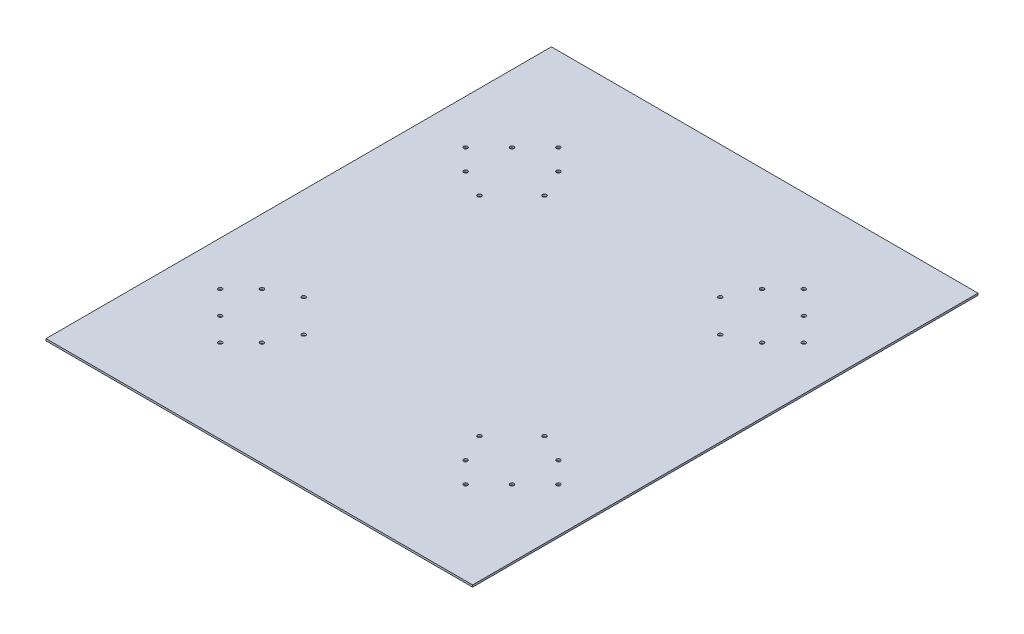
SolidWorks part; units mm, degrees
ref_plane "Front Plane" through (0, 0, 0) normal (0, 0, 1) x (1, 0, 0)
ref_plane "Top Plane" through (0, 0, 0) normal (0, 1, 0) x (1, 0, 0)
ref_plane "Right Plane" through (0, 0, 0) normal (1, 0, 0) x (0, 0, -1)
sketch "Sketch2" plane through (0, 1310.5484, 0) normal (0, 1, 0) x (1, 0, 0)
  line L0 (878.8182, -1232.4154) -> (956.6, -1310.1971) construction
  line L1 (740.7773, -1889.2272) -> (1390.7773, -1889.2272)
  line L2 (740.7773, -1889.2272) -> (740.7773, -1119.2272)
  line L3 (793.9654, -1691.1863) -> (878.8182, -1776.0391) construction
  line L4 (740.7773, -1119.2272) -> (1390.7773, -1119.2272)
  line L5 (1390.7773, -1889.2272) -> (1390.7773, -1119.2272)
  line L6 (740.7773, -1889.2272) -> (1390.7773, -1119.2272) construction
  line L7 (1337.5891, -1317.2682) -> (1252.7363, -1232.4154) construction
  line L11 (793.9654, -1691.1863) -> (878.8182, -1776.0391)
  line L15 (1337.5891, -1317.2682) -> (1252.7363, -1232.4154)
  line L16 (740.7773, -1119.2272) -> (1390.7773, -1889.2272) construction
  line L17 (836.3918, -1733.6127) -> (1295.1627, -1274.8418)
  line L18 (956.6, -1310.1971) -> (871.7472, -1395.0499) construction
  line L19 (871.7472, -1395.0499) -> (793.9654, -1317.2682) construction
  line L20 (793.9654, -1317.2682) -> (878.8182, -1232.4154) construction
  line L21 (1337.5891, -1317.2682) -> (1259.8074, -1395.0499) construction
  line L22 (1259.8074, -1395.0499) -> (1174.9546, -1310.1971) construction
  line L23 (1174.9546, -1310.1971) -> (1252.7363, -1232.4154) construction
  line L24 (1252.7363, -1232.4154) -> (1337.5891, -1317.2682) construction
  line L25 (1252.7363, -1776.0391) -> (1174.9546, -1698.2573) construction
  line L26 (1174.9546, -1698.2573) -> (1259.8074, -1613.4045) construction
  line L27 (1259.8074, -1613.4045) -> (1337.5891, -1691.1863) construction
  line L28 (1337.5891, -1691.1863) -> (1252.7363, -1776.0391) construction
  line L29 (871.7472, -1613.4045) -> (956.6, -1698.2573) construction
  line L30 (956.6, -1698.2573) -> (878.8182, -1776.0391) construction
  line L31 (878.8182, -1776.0391) -> (793.9654, -1691.1863) construction
  line L32 (793.9654, -1691.1863) -> (871.7472, -1613.4045) construction
  line L33 (878.8182, -1232.4154) -> (956.6, -1310.1971)
  line L34 (956.6, -1310.1971) -> (871.7472, -1395.0499)
  line L35 (871.7472, -1395.0499) -> (793.9654, -1317.2682)
  line L36 (793.9654, -1317.2682) -> (878.8182, -1232.4154)
  line L37 (1337.5891, -1317.2682) -> (1259.8074, -1395.0499)
  line L38 (1259.8074, -1395.0499) -> (1174.9546, -1310.1971)
  line L39 (1174.9546, -1310.1971) -> (1252.7363, -1232.4154)
  line L40 (1252.7363, -1232.4154) -> (1337.5891, -1317.2682)
  line L41 (1252.7363, -1776.0391) -> (1174.9546, -1698.2573)
  line L42 (1174.9546, -1698.2573) -> (1259.8074, -1613.4045)
  line L43 (1259.8074, -1613.4045) -> (1337.5891, -1691.1863)
  line L44 (1337.5891, -1691.1863) -> (1252.7363, -1776.0391)
  line L45 (871.7472, -1613.4045) -> (956.6, -1698.2573)
  line L46 (956.6, -1698.2573) -> (878.8182, -1776.0391)
  line L47 (878.8182, -1776.0391) -> (793.9654, -1691.1863)
  line L48 (793.9654, -1691.1863) -> (871.7472, -1613.4045)
  circle A1 centre (1249.2008, -1638.1533) radius 3
  circle A2 centre (1249.2008, -1638.1533) radius 3
  circle A3 centre (1199.7033, -1687.6507) radius 3
  circle A4 centre (1199.7033, -1687.6507) radius 3
  circle A5 centre (1220.9165, -1730.0771) radius 3
  circle A6 centre (1220.9165, -1730.0771) radius 3
  circle A7 centre (1252.7363, -1761.8969) radius 3
  circle A8 centre (1252.7363, -1761.8969) radius 3
  circle A9 centre (1288.0916, -1726.5416) radius 3
  circle A10 centre (1288.0916, -1726.5416) radius 3
  circle A11 centre (1323.447, -1691.1863) radius 3
  circle A12 centre (1323.447, -1691.1863) radius 3
  circle A13 centre (1291.6272, -1659.3665) radius 3
  circle A14 centre (1291.6272, -1659.3665) radius 3
  circle A15 centre (839.9274, -1659.3665) radius 3
  circle A16 centre (839.9274, -1659.3665) radius 3
  circle A17 centre (808.1076, -1691.1863) radius 3
  circle A18 centre (808.1076, -1691.1863) radius 3
  circle A19 centre (843.4629, -1726.5416) radius 3
  circle A20 centre (843.4629, -1726.5416) radius 3
  circle A21 centre (878.8182, -1761.8969) radius 3
  circle A22 centre (878.8182, -1761.8969) radius 3
  circle A23 centre (910.638, -1730.0771) radius 3
  circle A24 centre (910.638, -1730.0771) radius 3
  circle A25 centre (931.8512, -1687.6507) radius 3
  circle A26 centre (931.8512, -1687.6507) radius 3
  circle A27 centre (882.3538, -1638.1533) radius 3
  circle A28 centre (882.3538, -1638.1533) radius 3
  circle A29 centre (882.3538, -1370.3012) radius 3
  circle A30 centre (882.3538, -1370.3012) radius 3
  circle A31 centre (931.8512, -1320.8037) radius 3
  circle A32 centre (931.8512, -1320.8037) radius 3
  circle A33 centre (910.638, -1278.3773) radius 3
  circle A34 centre (910.638, -1278.3773) radius 3
  circle A35 centre (878.8182, -1246.5575) radius 3
  circle A36 centre (878.8182, -1246.5575) radius 3
  circle A37 centre (843.4629, -1281.9129) radius 3
  circle A38 centre (843.4629, -1281.9129) radius 3
  circle A39 centre (808.1076, -1317.2682) radius 3
  circle A40 centre (808.1076, -1317.2682) radius 3
  circle A41 centre (839.9274, -1349.088) radius 3
  circle A42 centre (839.9274, -1349.088) radius 3
  circle A43 centre (1199.7033, -1320.8037) radius 3
  circle A44 centre (1199.7033, -1320.8037) radius 3
  circle A45 centre (1249.2008, -1370.3012) radius 3
  circle A46 centre (1249.2008, -1370.3012) radius 3
  circle A47 centre (1291.6272, -1349.088) radius 3
  circle A48 centre (1291.6272, -1349.088) radius 3
  circle A49 centre (1323.447, -1317.2682) radius 3
  circle A50 centre (1323.447, -1317.2682) radius 3
  circle A51 centre (1288.0916, -1281.9129) radius 3
  circle A52 centre (1288.0916, -1281.9129) radius 3
  circle A53 centre (1252.7363, -1246.5575) radius 3
  circle A54 centre (1252.7363, -1246.5575) radius 3
  circle A55 centre (1220.9165, -1278.3773) radius 3
  circle A56 centre (1220.9165, -1278.3773) radius 3
  point P3 (1065.7773, -1504.2272)
  dimension "D1" = 770
  dimension "D2" = 650
  dimension "D3" = 0
  dimension "D4" = 0
  dimension "D5" = 0
  dimension "D6" = 0
  dimension "D7" = 0
  dimension "D8" = 0
  dimension "D9" = 0
  dimension "D10" = 0
  dimension "D11" = 0
  dimension "D12" = 0
  dimension "D13" = 0
  dimension "D14" = 0
  dimension "D15" = 0
  dimension "D16" = 0
  dimension "D17" = 0
  dimension "D18" = 0
  dimension "D19" = 0
  dimension "D20" = 0
  dimension "D21" = 0
  dimension "D22" = 0
  dimension "D23" = 0
  dimension "D24" = 0
  dimension "D25" = 0
  dimension "D26" = 0
  dimension "D27" = 0
  dimension "D28" = 0
  dimension "D29" = 0
  dimension "D30" = 0
extrude "Boss-Extrude2" add sketch "Sketch2" along normal blind 3
